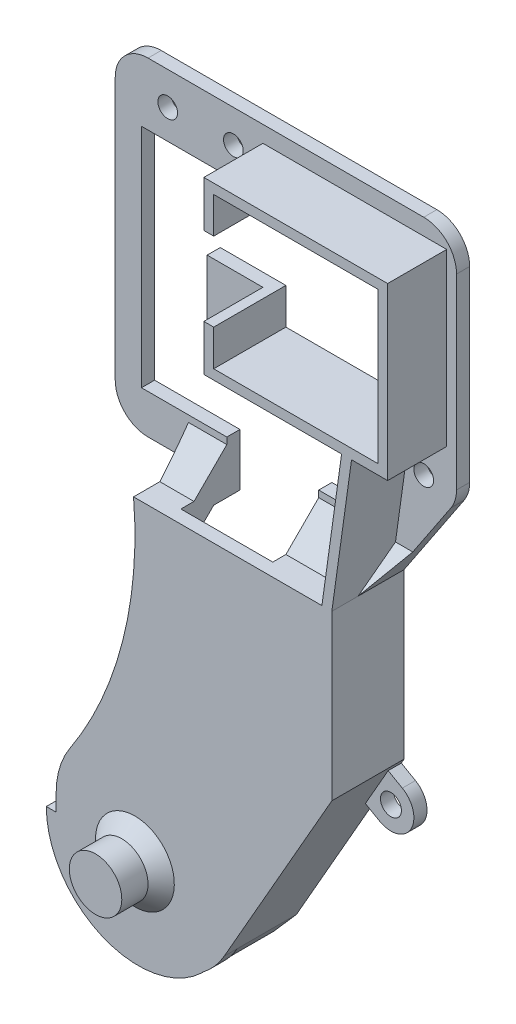
SolidWorks part; units mm, degrees
ref_plane "前视基准面" through (0, 0, 0) normal (0, 0, 1) x (1, 0, 0)
ref_plane "上视基准面" through (0, 0, 0) normal (0, 1, 0) x (1, 0, 0)
ref_plane "右视基准面" through (0, 0, 0) normal (1, 0, 0) x (0, 0, -1)
sketch "草图1" plane through (0, 0, 0) normal (1, 0, 0) x (0, 0, -1)
  line L0 (0, 0) -> (0, 58)
  line L1 (0, 58) -> (9, 58)
  line L2 (9, 58) -> (9, 110)
  line L3 (7, 110) -> (7, 60)
  line L4 (7, 60) -> (-2, 60)
  line L5 (-2, 60) -> (-2, 0)
  line L6 (-2, 0) -> (0, 0)
  line L7 (7, 110) -> (9, 110)
  point P9 (2.5, 60)
  dimension "D1" = 2
  dimension "D2" = 2
  dimension "D3" = 2
  dimension "D4" = 9
  dimension "D5" = 52
  dimension "D6" = 60
extrude "凸台-拉伸1" add sketch "草图1" along normal blind 52
sketch "草图2" plane through (0, 0, -7) normal (0, 0, 1) x (1, 0, 0)
  line L9 (52, 58) -> (0, 58) construction
  line L18 (24, 106) -> (49, 106)
  line L19 (24, 100.5) -> (24, 106)
  line L20 (4, 100.5) -> (24, 100.5)
  line L22 (4, 66) -> (4, 100.5)
  line L23 (17, 66) -> (4, 66)
  line L24 (17, 58) -> (17, 66)
  line L25 (31, 58) -> (17, 58)
  line L26 (31, 66) -> (31, 58)
  line L27 (41, 66) -> (31, 66)
  line L28 (41, 77) -> (41, 66)
  line L29 (14, 77) -> (41, 77)
  line L30 (14, 88.5) -> (14, 77)
  line L31 (24, 88.5) -> (14, 88.5)
  line L32 (24, 83) -> (24, 88.5)
  line L33 (49, 83) -> (24, 83)
  line L34 (49, 106) -> (49, 83)
  line L35 (52, 58) -> (52, 110) construction
  dimension "D1" = 23
  dimension "D2" = 12
  dimension "D3" = 5.5
  dimension "D4" = 10
  dimension "D5" = 6
  dimension "D6" = 17
  dimension "D7" = 25
  dimension "D8" = 25
  dimension "D9" = 8
  dimension "D10" = 20
  dimension "D11" = 10
  dimension "D12" = 10
  dimension "D13" = 3
  dimension "D14" = 14
extrude "切除-拉伸1" cut sketch "草图2" against normal up to next and the other way blind 7
sketch "草图3" plane through (0, 0, 2) normal (0, 0, 1) x (1, 0, 0)
  line L1 (16.7806, 105) -> (-11.2662, 105) construction
  line L2 (52, 110) -> (0, 110) construction
  line L5 (0, 0) -> (0, 60) construction
  line L6 (52, 0) -> (0, 0) construction
  line L7 (0, 60) -> (11.7913, 60)
  line L9 (0, 0) -> (0, 58) construction
  line L10 (42, 35) -> (42, 60)
  line L11 (52, 60) -> (0, 60) construction
  line L13 (0, 110) -> (0, 60) construction
  line L14 (0, 60) -> (0, 19)
  line L16 (42, 60) -> (52, 75)
  line L18 (52, 60) -> (0, 60) construction
  line L19 (52, 60) -> (31, 60) construction
  line L22 (42, 35) -> (22, 0)
  line L25 (52, 58) -> (52, 110) construction
  line L26 (52, 75) -> (52, 0)
  line L27 (52, 0) -> (22, 0)
  arc A17 (11.7913, 60) -> (0, 19) centre (-48, 55) cw
  circle A19 centre (8, 105) radius 1.5
  circle A20 centre (18, 105) radius 1.5
  circle A21 centre (47, 76) radius 1.5
  dimension "D4" = 3
  dimension "D5" = 10
  dimension "D6" = 22
  dimension "D8" = 25
  dimension "D9" = 3
  dimension "D10" = 5
  dimension "D11" = 8
  dimension "D12" = 16
  dimension "D13" = 15
  dimension "D1" = 60
  dimension "D2" = 3
  dimension "D14" = 5
  dimension "D3" = 55
  dimension "D7" = 48
  dimension "D15" = 10
extrude "切除-拉伸2" cut sketch "草图3" against normal through all
sketch "草图5" plane through (0, 0, 0) normal (0, 0, -1) x (-1, 0, 0)
  line L0 (-22, 0) -> (0, 0) construction
  line L1 (0, 19) -> (0, 0) construction
  circle A0 centre (-12, 12) radius 4
  dimension "D1" = 8
  dimension "D3" = 12
  dimension "D2" = 12
extrude "凸台-拉伸3" add sketch "草图5" against normal blind 8
fillet "圆角1" radius 5 4 edges at (52, 110, -8) (0, 110, -8) (52, 75, -8) (0, 60, -8)
chamfer "倒角1" distance 5 angle 45 2 edges at (14.3957, 60, -7) (36.5, 60, -7)
fillet "圆角2" radius 12.5 3 edges at (0, 0, 1) (22, 0, 1) (0, 19, 1)
sketch "草图4" plane through (0, 0, -7) normal (0, 0, 1) x (1, 0, 0)
  line L20 (24, 88.5) -> (24, 83)
  line L21 (24, 83) -> (49, 83)
  line L22 (49, 83) -> (49, 106)
  line L23 (49, 106) -> (24, 106)
  line L24 (24, 106) -> (24, 100.5)
  line L25 (24, 100.5) -> (22.5, 100.5)
  line L26 (24, 100.5) -> (4, 100.5) construction
  line L27 (22.5, 100.5) -> (22.5, 107.5)
  line L28 (22.5, 107.5) -> (50.5, 107.5)
  line L29 (50.5, 107.5) -> (50.5, 81.5)
  line L30 (50.5, 81.5) -> (45, 81.5)
  line L31 (22.5, 81.5) -> (22.5, 88.5)
  line L32 (14, 88.5) -> (24, 88.5) construction
  line L33 (22.5, 88.5) -> (24, 88.5)
  line L34 (40.4855, 60) -> (42, 60)
  line L35 (42, 60) -> (31, 60) construction
  line L36 (42, 60) -> (45, 81.5)
  line L38 (43.4855, 81.5) -> (40.4855, 60)
  line L39 (43.4855, 81.5) -> (22.5, 81.5)
  dimension "D7" = 1.5
  dimension "D8" = 1.5
  dimension "D9" = 1.5
  dimension "D10" = 1.5
  dimension "D11" = 1.5
  dimension "D12" = 5.5
extrude "凸台-拉伸2" add sketch "草图4" along normal blind 9
chamfer "倒角2" distance 5 angle 45 2 edges at (14.4625, 58, 0) (36.5, 58, 0)
sketch "草图6" plane through (0, 0, 0) normal (0, 0, -1) x (-1, 0, 0)
  line L0 (-40.5, 60) -> (-42, 60)
  line L1 (-42, 60) -> (-42, 35)
  line L2 (-42, 35) -> (-25.599, 6.2983)
  line L4 (-24.5728, 7.5257) -> (-40.5, 35.3983)
  line L5 (-40.5, 35.3983) -> (-40.5, 60)
  line L7 (-24.5728, 7.5257) -> (-20.5651, 2.95)
  line L8 (-25.599, 6.2983) -> (-22.1335, 2.3415)
  line L9 (1.5, 12.5) -> (0, 12.5)
  arc A2 (-20.5651, 2.95) -> (0, 12.5) centre (-12.5, 12.5) ccw
  arc A3 (-22.1335, 2.3415) -> (1.5, 12.5) centre (-12.5, 12.5) ccw
  dimension "D3" = 25
  dimension "D4" = 28
  dimension "D1" = 1.5
  dimension "D2" = 1.5
extrude "凸台-拉伸4" add sketch "草图6" along normal blind 9 and the other way blind 2
chamfer "倒角3" distance 2 angle 45 1 edges at (12, 16, 2)
sketch "草图7" plane through (0, 0, -9) normal (0, 0, -1) x (-1, 0, 0)
  line L0 (-41.5826, 34.2696) -> (-43.7365, 33.0389)
  line L1 (-42, 35) -> (-25.599, 6.2983) construction
  line L2 (-40.2635, 26.9611) -> (-38.1097, 28.1919)
  line L3 (-41.5826, 34.2696) -> (-38.1097, 28.1919)
  arc A0 (-43.7365, 33.0389) -> (-40.2635, 26.9611) centre (-42, 30) ccw
  circle A1 centre (-42, 30) radius 1.6
  dimension "D1" = 7
  dimension "D2" = 3.2
  dimension "D3" = 42
  dimension "D4" = 30
extrude "凸台-拉伸5" add sketch "草图7" against normal blind 2
